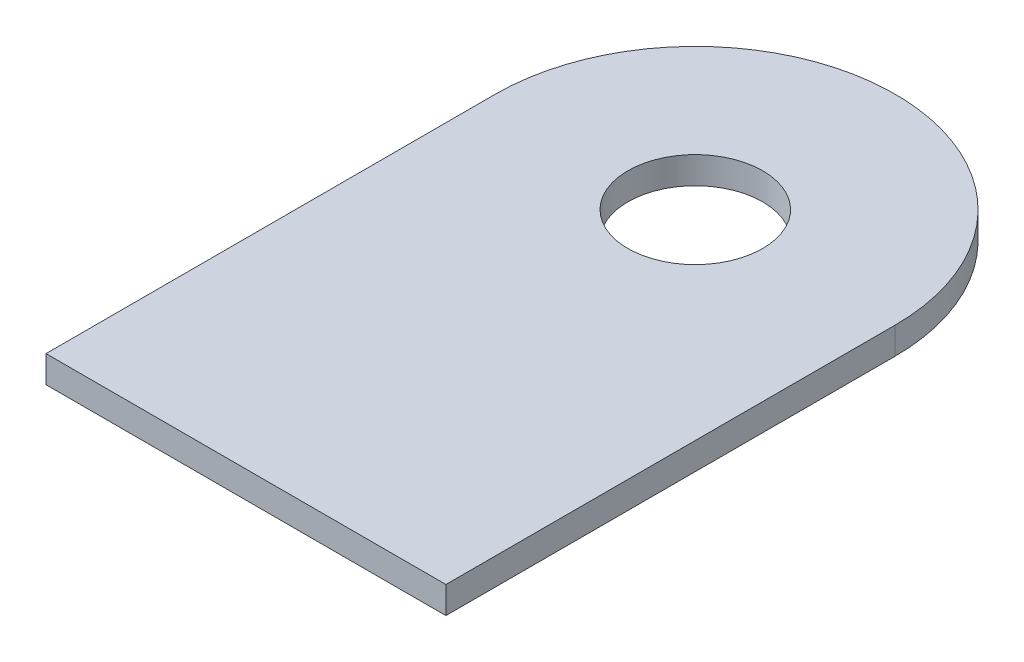
SolidWorks part; units mm, degrees
ref_plane "Front Plane" through (0, 0, 0) normal (0, 0, 1) x (1, 0, 0)
ref_plane "Top Plane" through (0, 0, 0) normal (0, 1, 0) x (1, 0, 0)
ref_plane "Right Plane" through (0, 0, 0) normal (1, 0, 0) x (0, 0, -1)
sketch "Sketch1" plane through (0, 0, 0) normal (0, 1, 0) x (1, 0, 0)
  line L1 (-11.303, -25.4) -> (11.303, -25.4)
  line L2 (-11.303, -25.4) -> (-11.303, 0)
  line L3 (-11.303, 0) -> (11.303, 0) construction
  line L4 (11.303, -25.4) -> (11.303, 0)
  circle A0 centre (0, 0) radius 3.81
  arc A1 (-11.303, 0) -> (11.303, 0) centre (0, 0) cw
  point P7 (0, -25.4)
  dimension "D1" = 7.62
  dimension "D2" = 25.4
  dimension "D3" = 22.606
extrude "Boss-Extrude1" add sketch "Sketch1" along normal blind 1.524
